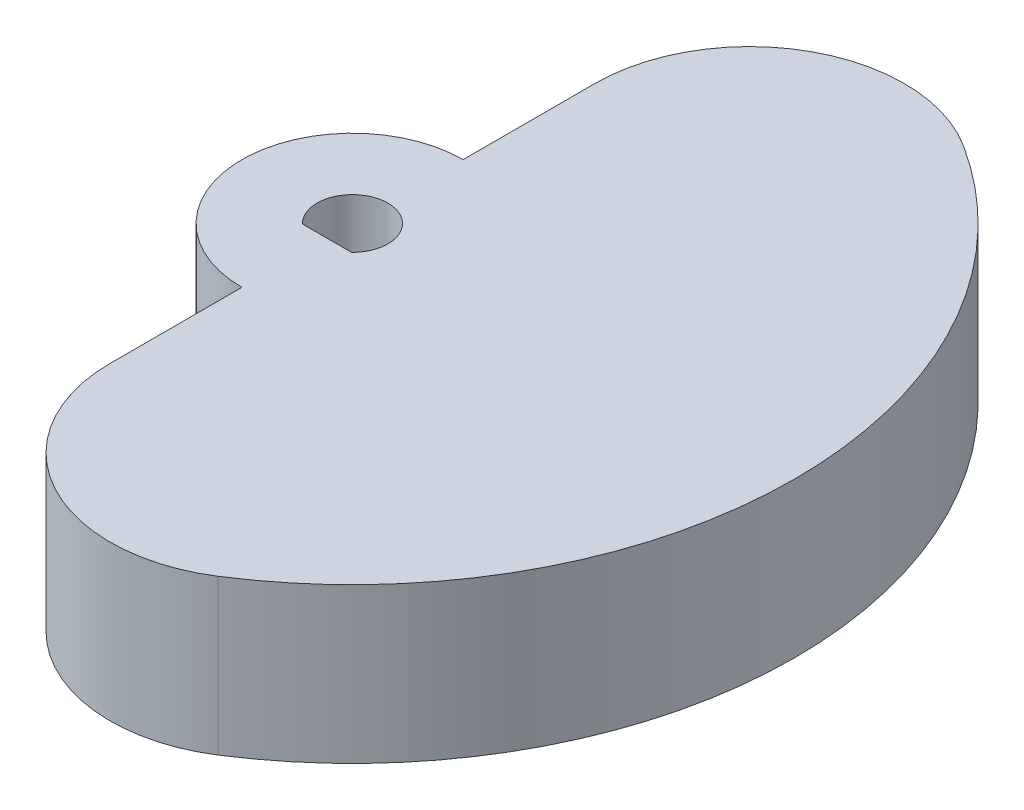
SolidWorks part; units mm, degrees
ref_plane "Front Plane" through (0, 0, 0) normal (0, 0, 1) x (1, 0, 0)
ref_plane "Top Plane" through (0, 0, 0) normal (0, 1, 0) x (1, 0, 0)
ref_plane "Right Plane" through (0, 0, 0) normal (1, 0, 0) x (0, 0, -1)
sketch "Sketch1" plane through (0, 0, 0) normal (0, 1, 0) x (1, 0, 0)
  line L1 (0, -1.15) -> (1.1124, -1.15) construction
  line L2 (1.1124, -1.15) -> (-1.1124, -1.15)
  line L5 (0, 20) -> (0, 5)
  line L8 (0, -5) -> (0, -20)
  arc A0 (1.1124, -1.15) -> (-1.1124, -1.15) centre (0, 0) ccw
  arc A1 (0, -20) -> (0, 20) centre (0, 0) ccw
  arc A2 (0, 5) -> (0, -5) centre (0, 0) ccw
  point P1 (0, 0)
  dimension "D1" = 3.2
  dimension "D3" = 40
  dimension "D4" = 10
extrude "Boss-Extrude1" add sketch "Sketch1" along normal blind 7
fillet "Fillet1" radius 7 2 edges at (0, 3.5, -20) (0, 3.5, 20)
